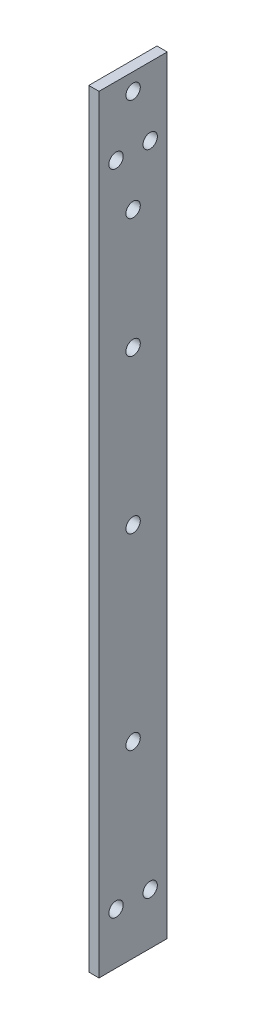
SolidWorks part; units mm, degrees
ref_plane "前视基准面" through (0, 0, 0) normal (0, 0, 1) x (1, 0, 0)
ref_plane "上视基准面" through (0, 0, 0) normal (0, 1, 0) x (1, 0, 0)
ref_plane "右视基准面" through (0, 0, 0) normal (1, 0, 0) x (0, 0, -1)
ref_plane "基准面4" through (-39, 0, 0) normal (-1, 0, 0) x (0, -1, 0)
sketch "草图1" plane through (-39, 0, 0) normal (-1, 0, 0) x (0, -1, 0)
  line L0 (-220, 0) -> (5, 0)
  line L1 (5, 0) -> (5, 20)
  line L2 (5, 20) -> (-220, 20)
  line L3 (-220, 20) -> (-220, 0)
  circle A0 centre (-215, 10) radius 2.1
  circle A1 centre (-200, 15) radius 2.1
  circle A2 centre (-185, 10) radius 2.1
  circle A3 centre (-10, 5) radius 2.1
  circle A4 centre (-10, 15) radius 2.1
  circle A5 centre (-200, 5) radius 2.1
  circle A6 centre (-150, 10) radius 2.1
  circle A7 centre (-105, 10) radius 2.1
  circle A8 centre (-50, 10) radius 2.1
extrude "凸台-拉伸1" add sketch "草图1" against normal blind 3
